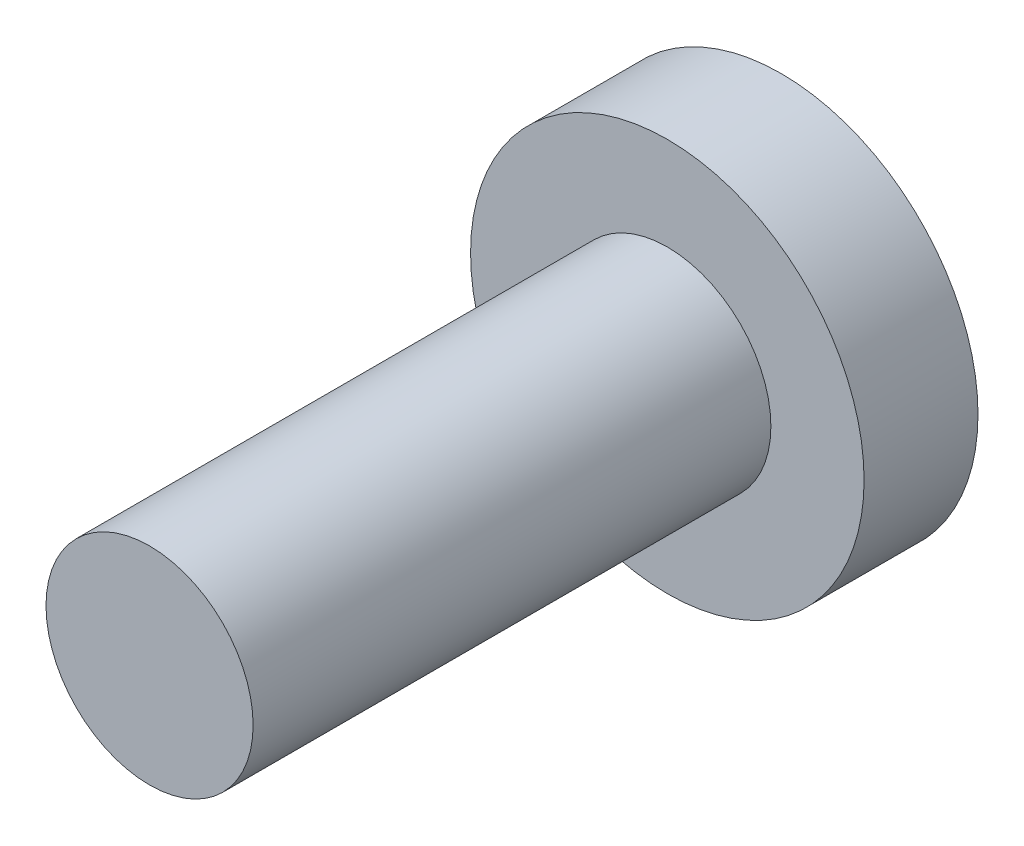
SolidWorks part; units mm, degrees
ref_plane "前视基准面" through (0, 0, 0) normal (0, 0, 1) x (1, 0, 0)
ref_plane "上视基准面" through (0, 0, 0) normal (0, 1, 0) x (1, 0, 0)
ref_plane "右视基准面" through (0, 0, 0) normal (1, 0, 0) x (0, 0, -1)
sketch "草图1" plane through (0, 0, 0) normal (0, 0, 1) x (1, 0, 0)
  circle A0 centre (0, 0) radius 3.8
extrude "凸台-拉伸1" add sketch "草图1" along normal blind 2.2
sketch "草图2" plane through (0, 0, 2.2) normal (0, 0, 1) x (1, 0, 0)
  circle A0 centre (0, 0) radius 2
extrude "凸台-拉伸2" add sketch "草图2" along normal blind 10
